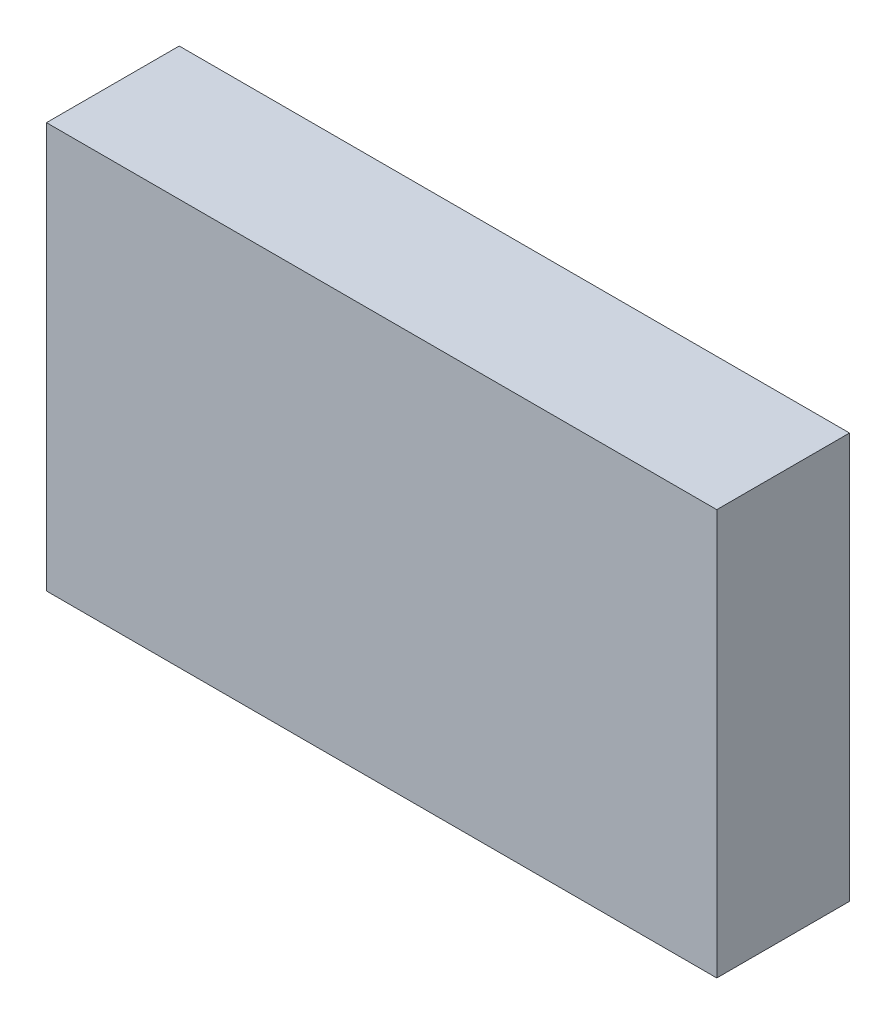
SolidWorks part; units mm, degrees
ref_plane "Front Plane" through (0, 0, 0) normal (0, 0, 1) x (1, 0, 0)
ref_plane "Top Plane" through (0, 0, 0) normal (0, 1, 0) x (1, 0, 0)
ref_plane "Right Plane" through (0, 0, 0) normal (1, 0, 0) x (0, 0, -1)
sketch "Sketch1" plane through (0, 0, 0) normal (0, 0, 1) x (1, 0, 0)
  line L1 (0, 0) -> (81.8, 0)
  line L2 (0, 0) -> (0, 49.5)
  line L3 (0, 49.5) -> (81.8, 49.5)
  line L4 (81.8, 0) -> (81.8, 49.5)
  dimension "D1" = 49.5
  dimension "D2" = 81.8
extrude "Boss-Extrude1" add sketch "Sketch1" along normal blind 16.2
